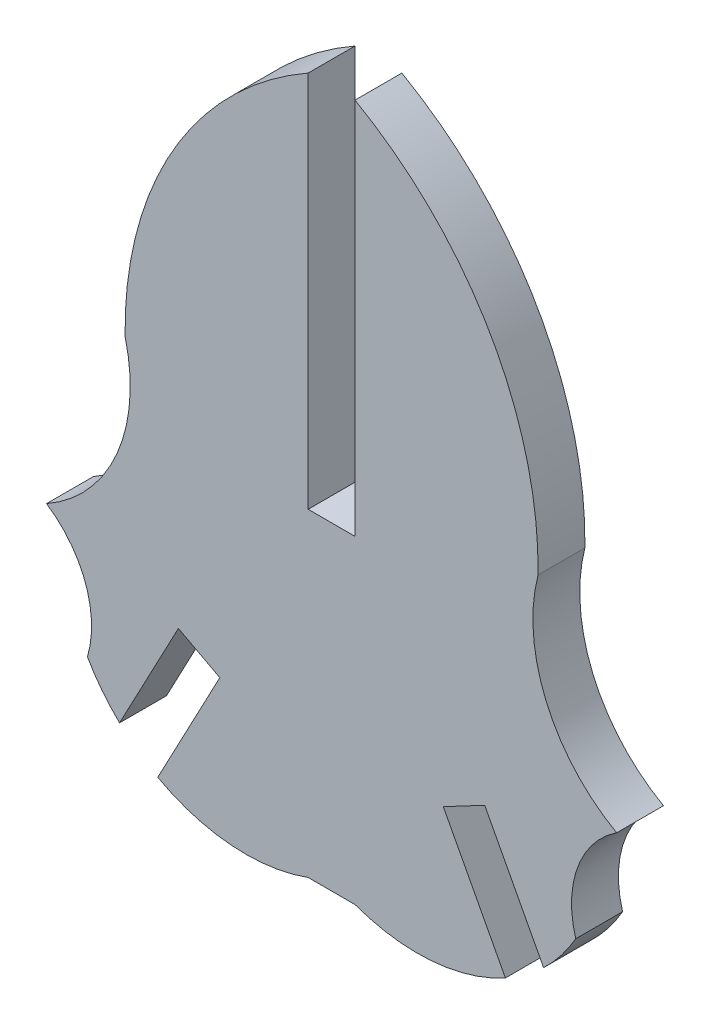
SolidWorks part; units mm, degrees
ref_plane "Front Plane" through (0, 0, 0) normal (0, 0, 1) x (1, 0, 0)
ref_plane "Top Plane" through (0, 0, 0) normal (0, 1, 0) x (1, 0, 0)
ref_plane "Right Plane" through (0, 0, 0) normal (1, 0, 0) x (0, 0, -1)
sketch "Sketch1" plane through (0, 0, 0) normal (0, 0, 1) x (1, 0, 0)
  line L0 (0, 114.8512) -> (1.524, 114.8512)
  line L1 (1.524, 114.8512) -> (0, 114.8512) construction
  line L2 (1.524, 114.8512) -> (1.524, 127.1375)
  line L3 (0, 104.4804) -> (1.524, 104.4804)
  line L4 (7.6567, 105.7695) -> (5.7426, 109.3863)
  line L5 (6.4149, 104.8577) -> (4.3956, 108.6735)
  line L6 (-4.2186, 109.3863) -> (-2.8716, 108.6735)
  line L7 (5.7426, 109.3863) -> (4.3956, 108.6735)
  line L8 (-4.8909, 104.8577) -> (-2.8716, 108.6735)
  line L9 (-6.1327, 105.7695) -> (-4.2186, 109.3863)
  line L10 (0, 114.8512) -> (0, 127.1375)
  arc A0 (1.524, 127.1375) -> (7.4767, 116.7403) centre (-4.2713, 116.9168) cw
  arc A1 (7.4767, 116.7403) -> (10.0327, 110.7565) centre (12.654, 115.414) ccw
  arc A2 (1.524, 104.4804) -> (6.4149, 104.8577) centre (3.5538, 110.0558) ccw
  arc A3 (8.7019, 107.1058) -> (10.0327, 110.7565) centre (11.8222, 108.0363) cw
  arc A4 (7.6567, 105.7695) -> (8.7019, 107.1058) centre (3.5538, 110.0558) ccw
  arc A5 (-6.1327, 105.7695) -> (-7.1779, 107.1058) centre (-2.0298, 110.0558) cw
  arc A6 (-7.1779, 107.1058) -> (-8.5087, 110.7565) centre (-10.2982, 108.0363) ccw
  arc A7 (0, 104.4804) -> (-4.8909, 104.8577) centre (-2.0298, 110.0558) cw
  arc A8 (-5.9527, 116.7403) -> (-8.5087, 110.7565) centre (-11.13, 115.414) cw
  arc A9 (0, 127.1375) -> (-5.9527, 116.7403) centre (5.7953, 116.9168) ccw
  point P17 (8.1502, 104.8368)
  point P19 (6.8032, 104.1239)
  point P37 (0.762, 114.8512)
extrude "Boss-Extrude1" add sketch "Sketch1" along normal blind 1.524
